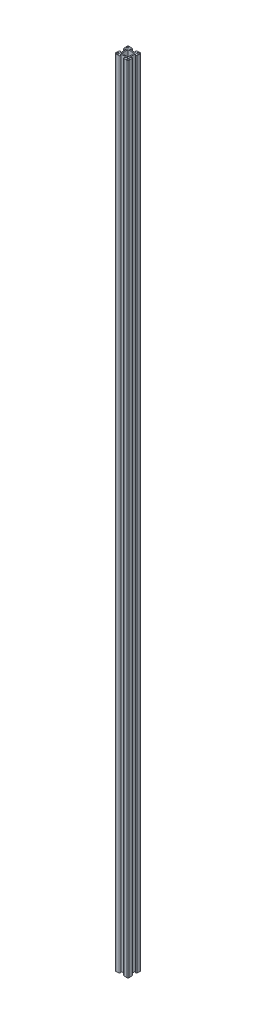
SolidWorks part; units mm, degrees
ref_plane "Front Plane" through (0, 0, 0) normal (0, 0, 1) x (1, 0, 0)
ref_plane "Top Plane" through (0, 0, 0) normal (0, 1, 0) x (1, 0, 0)
ref_plane "Right Plane" through (0, 0, 0) normal (1, 0, 0) x (0, 0, -1)
sketch "Sketch1" plane through (0, 0, 0) normal (0, 1, 0) x (1, 0, 0)
  line L1 (-16.2586, 10.8064) -> (9.1414, 10.8064)
  line L2 (-16.2586, 10.8064) -> (-16.2586, -14.5936)
  line L3 (-16.2586, -14.5936) -> (9.1414, -14.5936)
  line L4 (9.1414, 10.8064) -> (9.1414, -14.5936)
  dimension "D1" = 25.4
  dimension "D2" = 25.4
sketch "Sketch2" plane through (0, 0, 0) normal (0, 1, 0) x (1, 0, 0)
  line L0 (-19.5248, -1.8997) -> (12.956, -1.8997)
  line L1 (-3.2844, -16.3317) -> (-3.2844, 12.7118)
  line L2 (-16.2586, -14.5936) -> (9.1414, 10.8064)
  line L3 (-16.2586, 10.8064) -> (9.1414, -14.5936)
  line L4 (-16.2586, -14.5936) -> (-15.6079, -2.6453)
  line L8 (-1.665, 10.1557) -> (9.1414, 10.8064)
  line L9 (-16.2586, -14.5936) -> (-4.3104, -13.9428)
  line L10 (-4.3104, -13.9428) -> (-10.3408, -9.862)
  line L11 (-15.6079, -2.6453) -> (-11.6319, -8.6265)
  line L13 (8.4906, 0) -> (9.1414, 10.8064)
  line L16 (-4.2921, 10.1557) -> (-16.2586, 10.8064)
  line L18 (-2.8545, -13.9363) -> (9.1414, -14.5936)
  line L19 (8.4841, -2.5977) -> (4.4616, -8.4759)
  line L20 (-15.6079, -1.1601) -> (-11.6319, 4.8561)
  line L21 (-2.8545, -13.9363) -> (3.3396, -9.862)
  line L22 (-15.6079, -1.1601) -> (-16.2586, 10.8064)
  line L23 (8.4841, -2.5977) -> (9.1414, -14.5936)
  line L25 (8.4906, 0) -> (4.4616, 4.6752)
  line L26 (4.4616, -9.862) -> (-11.6319, -9.862)
  line L27 (4.4616, -9.862) -> (4.4616, 6.2316)
  line L28 (4.4616, 6.2316) -> (-11.6319, 6.2316)
  line L29 (-11.6319, -9.862) -> (-11.6319, 6.2316)
  line L30 (-1.665, 10.1557) -> (3.012, 6.2316)
  line L31 (-4.2921, 10.1557) -> (-10.2576, 6.2316)
  line L32 (3.1916, -8.592) -> (3.1916, 4.9616)
  line L33 (3.1916, 4.9616) -> (-10.3619, 4.9616)
  line L34 (-10.3619, -8.592) -> (-10.3619, 4.9616)
  line L35 (3.1916, -8.592) -> (-10.3619, -8.592)
  line L36 (4.4616, -8.4759) -> (3.3396, -9.862)
  line L37 (-10.3408, -9.862) -> (-11.6319, -8.6265)
  line L38 (4.4616, 4.6752) -> (3.012, 6.2316)
  line L39 (-10.2576, 6.2316) -> (-11.6319, 4.8561)
  dimension "D1" = 1.27
extrude "Boss-Extrude1" add sketch "Sketch2" along normal blind 1510
fillet "Fillet1" radius 2.032 4 edges at (9.1414, 755, 14.5936) (9.1414, 755, -10.8064) (-16.2586, 755, -10.8064) (-16.2586, 755, 14.5936)
fillet "Fillet2" radius 1.27 8 edges at (-15.6079, 755, 2.6453) (-15.6079, 755, 1.1601) (-4.3104, 755, 13.9428) (-4.2921, 755, -10.1557) (-1.665, 755, -10.1557) (8.4906, 755, 0) (8.4841, 755, 2.5977) (-2.8545, 755, 13.9363)
sketch "Sketch5" plane through (0, 1510, 0) normal (0, 1, 0) x (1, 0, 0)
  line L1 (2.4309, 4.0973) -> (-9.6178, 4.0973)
  line L2 (2.4309, 4.0973) -> (2.4309, -7.8996)
  line L3 (2.4309, -7.8996) -> (-9.6178, -7.8996)
  line L4 (-9.6178, 4.0973) -> (-9.6178, -7.8996)
  circle A0 centre (5.9214, 7.6654) radius 1.7848
  circle A1 centre (6.0507, -11.416) radius 1.8099
  circle A2 centre (-13.1083, 7.6137) radius 1.778
  circle A3 centre (-13.0307, -11.5453) radius 1.778
extrude "Cut-Extrude3" cut sketch "Sketch5" against normal through all contours L1 L4 L3 L2 | A1 | A3 | A2 | A0
scale "Scale1" bodies to scale 124 scale about centroid uniform scaling yes scale factor 0.8
